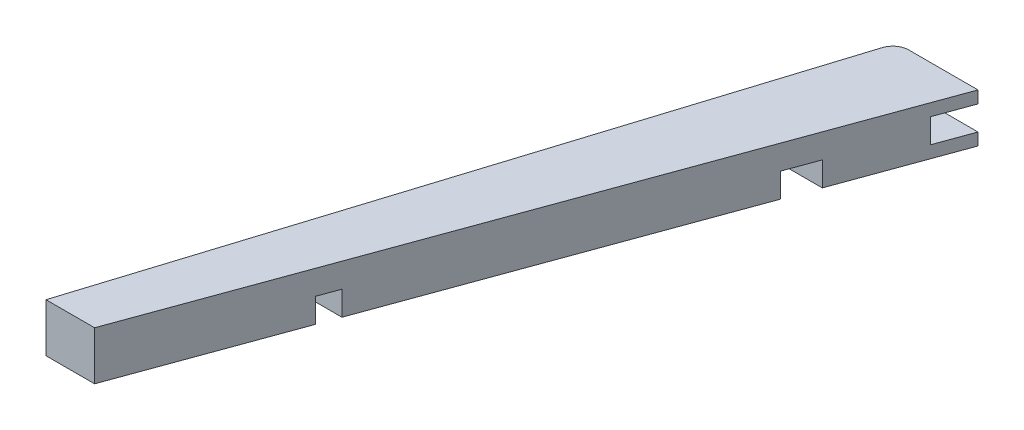
SolidWorks part; units mm, degrees
ref_plane "Alzado" through (0, 0, 0) normal (0, 0, 1) x (1, 0, 0)
ref_plane "Planta" through (0, 0, 0) normal (0, 1, 0) x (1, 0, 0)
ref_plane "Vista lateral" through (0, 0, 0) normal (1, 0, 0) x (0, 0, -1)
sketch "Croquis1" plane through (0, 0, 0) normal (0, 1, 0) x (1, 0, 0)
  line L8 (15, 0) -> (160.5881, 400)
  line L9 (160.5881, 400) -> (110.5881, 400)
  line L10 (110.5881, 400) -> (-15, 0)
  line L11 (-15, 0) -> (15, 0)
  point P6 (0, 0)
  dimension "D1" = 50
  dimension "D2" = 30
  dimension "D3" = 110
  dimension "D4" = 400
extrude "Saliente-Extruir1" add sketch "Croquis1" along normal mid plane 30
sketch "Croquis2" plane through (0, 0, -400) normal (0, 0, -1) x (-1, 0, 0)
  line L0 (-160.5881, 15) -> (-160.5881, -15) construction
  line L1 (-160.5881, 7.5) -> (-135.5881, 7.5)
  line L2 (-160.5881, 7.5) -> (-160.5881, -7.5)
  line L3 (-160.5881, -7.5) -> (-135.5881, -7.5)
  line L4 (-135.5881, 7.5) -> (-135.5881, -7.5)
  line L5 (-110.5881, 15) -> (-110.5881, -15) construction
  line L6 (-160.5881, 15) -> (-110.5881, 15) construction
  point P8 (-110.5881, 0)
  point P9 (-135.5881, 0)
  point P12 (-135.5881, 15)
  dimension "D1" = 15
extrude "Cortar-Extruir1" cut sketch "Croquis2" against normal blind 21.55
fillet "Redondeo2" radius 10 1 edges at (110.5881, 0, -400)
sketch "Croquis3" plane through (0, 15, 0) normal (0, 1, 0) x (1, 0, 0)
  line L0 (15, 0) -> (160.5881, 400) construction
  line L1 (111.4705, 329.5) -> (151.4705, 329.5)
  line L2 (111.4705, 329.5) -> (111.4705, 310.5)
  line L3 (111.4705, 310.5) -> (151.4705, 310.5)
  line L4 (151.4705, 329.5) -> (151.4705, 310.5)
  line L5 (111.4705, 329.5) -> (151.4705, 310.5) construction
  line L6 (111.4705, 310.5) -> (151.4705, 329.5) construction
  line L8 (33.5808, 112) -> (73.5808, 112)
  line L9 (33.5808, 112) -> (33.5808, 100)
  line L10 (33.5808, 100) -> (73.5808, 100)
  line L11 (73.5808, 112) -> (73.5808, 100)
  line L12 (33.5808, 112) -> (73.5808, 100) construction
  line L13 (33.5808, 100) -> (73.5808, 112) construction
  point P0 (131.4705, 320)
  point P7 (53.5808, 106)
  dimension "D1" = 19
  dimension "D2" = 20
  dimension "D3" = 12
  dimension "D4" = 20
  dimension "D5" = 80
  dimension "D6" = 100
sketch "Croquis5" plane through (0, -15, 0) normal (0, -1, 0) x (1, 0, 0)
  line L4 (33.5808, -112) -> (73.5808, -112)
  line L5 (73.5808, -112) -> (73.5808, -100)
  line L6 (73.5808, -100) -> (33.5808, -100)
  line L7 (33.5808, -100) -> (33.5808, -112)
  line L8 (33.5808, -112) -> (73.5808, -112)
  line L9 (73.5808, -112) -> (73.5808, -100)
  line L10 (73.5808, -100) -> (33.5808, -100)
  line L11 (33.5808, -100) -> (33.5808, -112)
  line L12 (111.4705, -329.5) -> (151.4705, -329.5)
  line L13 (151.4705, -329.5) -> (151.4705, -310.5)
  line L14 (151.4705, -310.5) -> (111.4705, -310.5)
  line L15 (111.4705, -310.5) -> (111.4705, -329.5)
  line L16 (111.4705, -329.5) -> (151.4705, -329.5)
  line L17 (151.4705, -329.5) -> (151.4705, -310.5)
  line L18 (151.4705, -310.5) -> (111.4705, -310.5)
  line L19 (111.4705, -310.5) -> (111.4705, -329.5)
  dimension "D1" = 0
  dimension "D2" = 0
extrude "Cortar-Extruir3" cut sketch "Croquis5" against normal blind 15
sketch "Croquis6" [suppressed] plane through (0, 15, 0) normal (0, 1, 0) x (1, 0, 0)
  line L0 (151.4705, 329.5) -> (151.4705, 310.5) construction
  line L1 (111.4705, 329.5) -> (151.4705, 329.5) construction
  line L2 (111.4705, 329.5) -> (111.4705, 310.5) construction
  line L3 (111.4705, 310.5) -> (151.4705, 310.5) construction
  line L4 (33.5808, 112) -> (33.5808, 100) construction
  line L5 (33.5808, 112) -> (73.5808, 112) construction
  line L6 (73.5808, 112) -> (73.5808, 100) construction
  line L7 (33.5808, 100) -> (73.5808, 100) construction
  line L8 (151.4705, 329.5) -> (151.4705, 310.5)
  line L9 (111.4705, 329.5) -> (151.4705, 329.5)
  line L10 (111.4705, 329.5) -> (111.4705, 310.5)
  line L11 (111.4705, 310.5) -> (151.4705, 310.5)
  line L12 (33.5808, 112) -> (33.5808, 100)
  line L13 (33.5808, 112) -> (73.5808, 112)
  line L14 (73.5808, 112) -> (73.5808, 100)
  line L15 (33.5808, 100) -> (73.5808, 100)
extrude "Cortar-Extruir4" [suppressed] cut sketch "Croquis6" against normal blind 15
